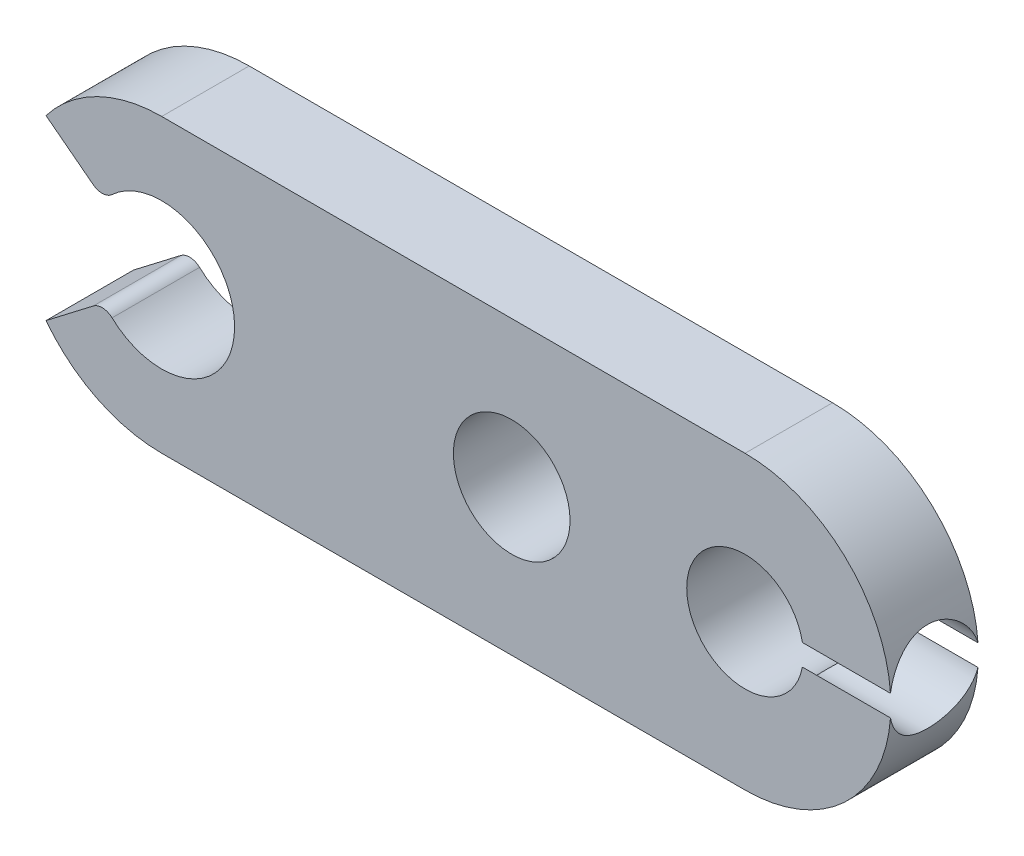
SolidWorks part; units mm, degrees
ref_plane "Front Plane" through (0, 0, 0) normal (0, 0, 1) x (1, 0, 0)
ref_plane "Top Plane" through (0, 0, 0) normal (0, 1, 0) x (1, 0, 0)
ref_plane "Right Plane" through (0, 0, 0) normal (1, 0, 0) x (0, 0, -1)
sketch "Sketch1" plane through (0, 0, 0) normal (0, 0, 1) x (1, 0, 0)
  line L0 (-3.9668, 3.0438) -> (-1.9834, 1.5219)
  line L1 (-1.9834, -1.5219) -> (-3.9668, -3.0438)
  line L2 (0, 5) -> (20, 5)
  line L3 (20, -5) -> (0, -5)
  arc A0 (-3.9668, 3.0438) -> (0, 5) centre (0, 0) cw
  arc A1 (-1.9834, 1.5219) -> (-1.9834, -1.5219) centre (0, 0) cw
  arc A2 (20, 5) -> (20, -5) centre (20, 0) cw
  arc A3 (0, -5) -> (-3.9668, -3.0438) centre (0, 0) cw
  dimension "D2" = 2.5
  dimension "D3" = 5
  dimension "D4" = 20
  dimension "D1" = 75
extrude "Boss-Extrude1" add sketch "Sketch1" along normal blind 3
fillet "Fillet1" radius 0.5 2 edges at (-1.9834, 1.5219, 1.5) (-1.9834, -1.5219, 1.5)
sketch "Sketch2" plane through (0, 0, 3) normal (0, 0, 1) x (1, 0, 0)
  circle A0 centre (20, 0) radius 2
  arc A1 (20, -5) -> (20, 5) centre (20, 0) ccw construction
  arc A2 (20, -5) -> (20, 5) centre (20, 0) ccw construction
  dimension "D1" = 4
extrude "Cut-Extrude1" cut sketch "Sketch2" against normal blind 10
sketch "Sketch3" plane through (0, 0, 3) normal (0, 0, 1) x (1, 0, 0)
  circle A2 centre (12, 0) radius 2
  dimension "D1" = 4
  dimension "D2" = 12
extrude "Cut-Extrude2" cut sketch "Sketch3" against normal up to vertex (3 mm away) up to point (0, 0, 0)
sketch "Sketch4" plane through (0, 0, 0) normal (1, 0, 0) x (0, 0, -1)
  line L0 (-1.5, 0) -> (-1.5, 5) construction
  line L1 (-3, 5) -> (0, 5) construction
  circle A0 centre (-1.5, 0) radius 1.5437
  dimension "D1" = 3.0875
extrude "Cut-Extrude3" cut sketch "Sketch4" against normal blind 30 from offset 50
sketch "Sketch5" plane through (0, 0, 0) normal (0, 0, -1) x (-1, 0, 0)
  line L19 (-21.6086, -3.6623) -> (-23.4041, -3.6623)
  line L20 (0, -4) -> (-20, -4)
  line L21 (3, -4) -> (-20, -4)
  line L23 (0, -5) -> (-20, -5)
  line L24 (0, -5) -> (-20, -5) construction
  line L25 (0, -5) -> (3, -5)
  line L30 (3, -5) -> (3, -4)
  arc A25 (-24.9867, -0.3649) -> (-20, -5) centre (-20, 0) ccw construction
  arc A26 (-23.9893, -0.2919) -> (-20, -4) centre (-20, 0) ccw
  arc A27 (-21.6086, -3.6623) -> (-20, -4) centre (-20, 0) ccw
  arc A28 (-20, -5) -> (-23.4041, -3.6623) centre (-20, 0) cw
  arc A29 (0, -5) -> (3.9668, -3.0438) centre (0, 0) ccw construction
  dimension "D1" = 1
ref_plane "Plane1" through (0, 0, 1.5) normal (0, 0, -1) x (-1, 0, 0)
extrude "Cut-Extrude4" cut sketch "Sketch5" against normal mid plane 1 from surface at -1.5 starting at plane "Plane1"
